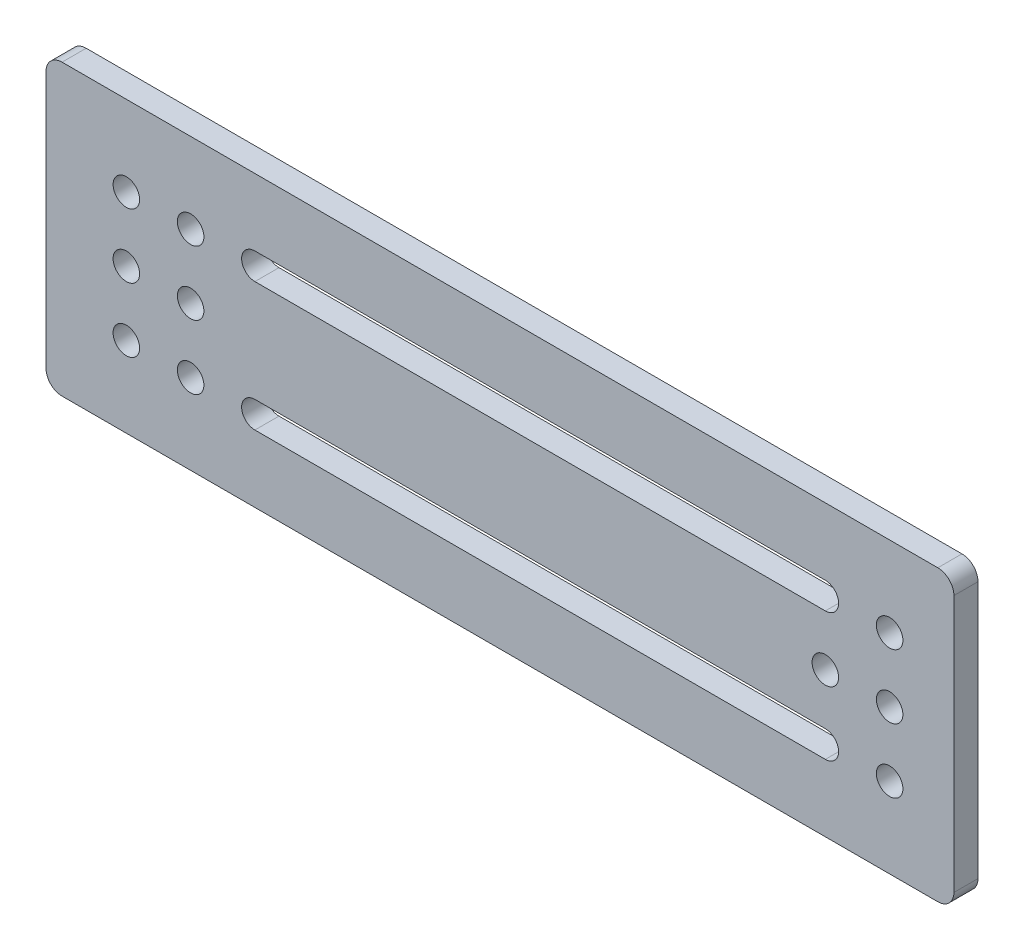
SolidWorks part; units mm, degrees
ref_plane "前视基准面" through (0, 0, 0) normal (0, 0, 1) x (1, 0, 0)
ref_plane "上视基准面" through (0, 0, 0) normal (0, 1, 0) x (1, 0, 0)
ref_plane "右视基准面" through (0, 0, 0) normal (1, 0, 0) x (0, 0, -1)
sketch "草图1" plane through (0, 0, 0) normal (0, 0, 1) x (1, 0, 0)
  line L0 (26, 27.65) -> (97, 27.65)
  line L1 (0, 0) -> (113, 0)
  line L2 (0, 0) -> (0, 36)
  line L3 (0, 36) -> (113, 36)
  line L4 (113, 0) -> (113, 36)
  line L5 (97, 27.65) -> (97, 24.35)
  line L6 (97, 24.35) -> (26, 24.35)
  line L7 (26, 11.65) -> (97, 11.65)
  line L8 (10, 18) -> (14.125, 18)
  line L9 (97, 11.65) -> (97, 8.35)
  line L10 (97, 8.35) -> (26, 8.35)
  circle A0 centre (10, 26) radius 1.65
  circle A1 centre (10, 10) radius 1.65
  circle A2 centre (10, 18) radius 1.65
  circle A3 centre (105, 18) radius 1.65
  circle A4 centre (105, 10) radius 1.65
  circle A5 centre (105, 26) radius 1.65
  circle A7 centre (97, 26) radius 1.65
  circle A10 centre (97, 10) radius 1.65
  circle A12 centre (97, 18) radius 1.65
  circle A13 centre (18, 18) radius 1.65
  circle A14 centre (18, 26) radius 1.65
  circle A15 centre (18, 10) radius 1.65
  circle A16 centre (26, 10) radius 1.65
  circle A17 centre (26, 26) radius 1.65
extrude "凸台-拉伸1" add sketch "草图1" along normal blind 3
fillet "圆角1" radius 2 4 edges at (0, 0, 1.5) (113, 0, 1.5) (113, 36, 1.5) (0, 36, 1.5)
